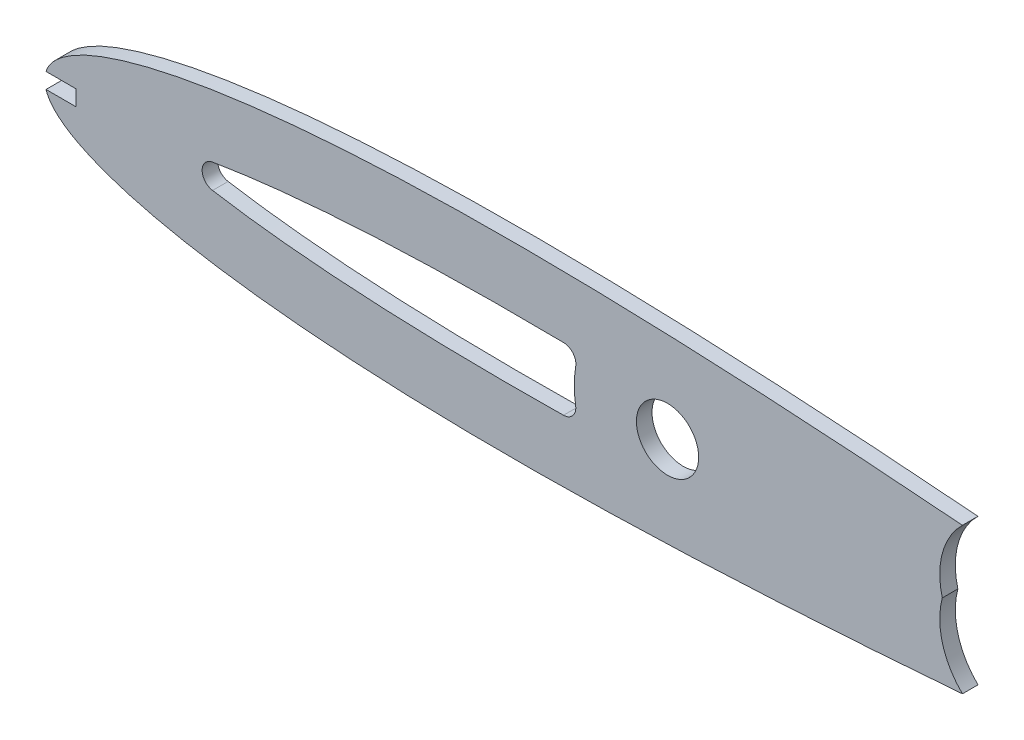
SolidWorks part; units mm, degrees
material "Balsa"
ref_plane "Front Plane" through (0, 0, 0) normal (0, 0, 1) x (1, 0, 0)
ref_plane "Top Plane" through (0, 0, 0) normal (0, 1, 0) x (1, 0, 0)
ref_plane "Right Plane" through (0, 0, 0) normal (1, 0, 0) x (0, 0, -1)
curve "Curve1"
  spline degree 3 poles (318.9616, -0.5388, 0) (318.9616, 0.5388, 0) (317.8871, 0.4072, 0) (316.5257, 0.7904, 0) (314.029, 1.0273, 0) (310.6656, 1.5357, 0) (306.333, 2.103, 0) (301.1081, 2.8022, 0) (295.0047, 3.5926, 0) (288.0667, 4.4725, 0) (280.3349, 5.4267, 0) (271.8575, 6.4421, 0) (262.6867, 7.5062, 0) (252.8789, 8.6045, 0) (242.4947, 9.7236, 0) (231.5982, 10.8496, 0) (220.2564, 11.9679, 0) (208.5394, 13.0629, 0) (196.5193, 14.1202, 0) (184.2704, 15.122, 0) (171.8679, 16.0521, 0) (159.3884, 16.8933, 0) (146.9087, 17.6278, 0) (134.5058, 18.2372, 0) (122.2562, 18.7052, 0) (110.2351, 19.0165, 0) (98.5168, 19.156, 0) (87.1732, 19.1125, 0) (76.2743, 18.8777, 0) (65.8873, 18.4456, 0) (56.076, 17.8151, 0) (46.9007, 16.9881, 0) (38.4176, 15.971, 0) (30.6784, 14.7725, 0) (23.73, 13.4051, 0) (17.6131, 11.8842, 0) (12.3624, 10.2248, 0) (8.0047, 8.4423, 0) (4.5539, 6.5486, 0) (2.0152, 4.5401, 0) (0.3892, 2.3682, 0) (-0.1814, 0, 0) (0.3892, -2.3682, 0) (2.0152, -4.5401, 0) (4.5539, -6.5486, 0) (8.0047, -8.4423, 0) (12.3624, -10.2248, 0) (17.6131, -11.8842, 0) (23.73, -13.4051, 0) (30.6784, -14.7725, 0) (38.4176, -15.971, 0) (46.9007, -16.9881, 0) (56.076, -17.8151, 0) (65.8873, -18.4456, 0) (76.2743, -18.8777, 0) (87.1732, -19.1125, 0) (98.5168, -19.156, 0) (110.2351, -19.0165, 0) (122.2562, -18.7052, 0) (134.5058, -18.2372, 0) (146.9087, -17.6278, 0) (159.3884, -16.8933, 0) (171.8679, -16.0521, 0) (184.2704, -15.122, 0) (196.5193, -14.1202, 0) (208.5394, -13.0629, 0) (220.2564, -11.9679, 0) (231.5982, -10.8496, 0) (242.4947, -9.7236, 0) (252.8789, -8.6045, 0) (262.6867, -7.5062, 0) (271.8575, -6.4421, 0) (280.3349, -5.4267, 0) (288.0667, -4.4725, 0) (295.0047, -3.5926, 0) (301.1081, -2.8022, 0) (306.333, -2.103, 0) (310.6656, -1.5357, 0) (314.029, -1.0273, 0) (316.5257, -0.7904, 0) (317.8871, -0.4072, 0) (318.9616, -0.5388, 0) (318.9616, 0.5388, 0) (317.8871, 0.4072, 0) knots -0.004279 -0.001997 -0.001234 0 0.000762 0.003045 0.006832 0.012101 0.018818 0.026939 0.036415 0.047185 0.05918 0.072328 0.086544 0.101741 0.117823 0.134691 0.15224 0.170361 0.188941 0.207865 0.227016 0.246276 0.265525 0.284645 0.30352 0.322035 0.340078 0.357543 0.374325 0.39033 0.405464 0.419644 0.432793 0.444844 0.455738 0.465429 0.473886 0.481102 0.487102 0.491975 0.495931 0.499383 0.502835 0.50679 0.511664 0.517664 0.524879 0.533337 0.543028 0.553922 0.565972 0.579122 0.593302 0.608436 0.62444 0.641223 0.658687 0.676731 0.695245 0.714121 0.733241 0.75249 0.77175 0.7909 0.809825 0.828404 0.846525 0.864074 0.880942 0.897025 0.912222 0.926438 0.939585 0.951581 0.962351 0.971826 0.979948 0.986664 0.991933 0.995721 0.998003 0.998766 1 1.000762 1.003045 1.006832 periodic
sketch "Sketch2" plane through (0, 0, 0) normal (0, 0, 1) x (1, 0, 0)
  spline S0 degree 3 poles (318.9616, -0.5388) (318.9616, 0.5388) (317.8871, 0.4072) (316.5257, 0.7904) (314.029, 1.0273) (310.6656, 1.5357) (306.333, 2.103) (301.1081, 2.8022) (295.0047, 3.5926) (288.0667, 4.4725) (280.3349, 5.4267) (271.8575, 6.4421) (262.6867, 7.5062) (252.8789, 8.6045) (242.4947, 9.7236) (231.5982, 10.8496) (220.2564, 11.9679) (208.5394, 13.0629) (196.5193, 14.1202) (184.2704, 15.122) (171.8679, 16.0521) (159.3884, 16.8933) (146.9087, 17.6278) (134.5058, 18.2372) (122.2562, 18.7052) (110.2351, 19.0165) (98.5168, 19.156) (87.1732, 19.1125) (76.2743, 18.8777) (65.8873, 18.4456) (56.076, 17.8151) (46.9007, 16.9881) (38.4176, 15.971) (30.6784, 14.7725) (23.73, 13.4051) (17.6131, 11.8842) (12.3624, 10.2248) (8.0047, 8.4423) (4.5539, 6.5486) (2.0152, 4.5401) (0.3892, 2.3682) (-0.1814, 0) (0.3892, -2.3682) (2.0152, -4.5401) (4.5539, -6.5486) (8.0047, -8.4423) (12.3624, -10.2248) (17.6131, -11.8842) (23.73, -13.4051) (30.6784, -14.7725) (38.4176, -15.971) (46.9007, -16.9881) (56.076, -17.8151) (65.8873, -18.4456) (76.2743, -18.8777) (87.1732, -19.1125) (98.5168, -19.156) (110.2351, -19.0165) (122.2562, -18.7052) (134.5058, -18.2372) (146.9087, -17.6278) (159.3884, -16.8933) (171.8679, -16.0521) (184.2704, -15.122) (196.5193, -14.1202) (208.5394, -13.0629) (220.2564, -11.9679) (231.5982, -10.8496) (242.4947, -9.7236) (252.8789, -8.6045) (262.6867, -7.5062) (271.8575, -6.4421) (280.3349, -5.4267) (288.0667, -4.4725) (295.0047, -3.5926) (301.1081, -2.8022) (306.333, -2.103) (310.6656, -1.5357) (314.029, -1.0273) (316.5257, -0.7904) (317.8871, -0.4072) (318.9616, -0.5388) (318.9616, 0.5388) (317.8871, 0.4072) knots -0.004279 -0.001997 -0.001234 0 0.000762 0.003045 0.006832 0.012101 0.018818 0.026939 0.036415 0.047185 0.05918 0.072328 0.086544 0.101741 0.117823 0.134691 0.15224 0.170361 0.188941 0.207865 0.227016 0.246276 0.265525 0.284645 0.30352 0.322035 0.340078 0.357543 0.374325 0.39033 0.405464 0.419644 0.432793 0.444844 0.455738 0.465429 0.473886 0.481102 0.487102 0.491975 0.495931 0.499383 0.502835 0.50679 0.511664 0.517664 0.524879 0.533337 0.543028 0.553922 0.565972 0.579122 0.593302 0.608436 0.62444 0.641223 0.658687 0.676731 0.695245 0.714121 0.733241 0.75249 0.77175 0.7909 0.809825 0.828404 0.846525 0.864074 0.880942 0.897025 0.912222 0.926438 0.939585 0.951581 0.962351 0.971826 0.979948 0.986664 0.991933 0.995721 0.998003 0.998766 1 1.000762 1.003045 1.006832 only from (318.77, 0.4017) to (318.77, 0.4017) construction
  spline S1 degree 3 poles (318.9616, -0.5388) (318.9616, 0.5388) (317.8871, 0.4072) (316.5257, 0.7904) (314.029, 1.0273) (310.6656, 1.5357) (306.333, 2.103) (301.1081, 2.8022) (295.0047, 3.5926) (288.0667, 4.4725) (280.3349, 5.4267) (271.8575, 6.4421) (262.6867, 7.5062) (252.8789, 8.6045) (242.4947, 9.7236) (231.5982, 10.8496) (220.2564, 11.9679) (208.5394, 13.0629) (196.5193, 14.1202) (184.2704, 15.122) (171.8679, 16.0521) (159.3884, 16.8933) (146.9087, 17.6278) (134.5058, 18.2372) (122.2562, 18.7052) (110.2351, 19.0165) (98.5168, 19.156) (87.1732, 19.1125) (76.2743, 18.8777) (65.8873, 18.4456) (56.076, 17.8151) (46.9007, 16.9881) (38.4176, 15.971) (30.6784, 14.7725) (23.73, 13.4051) (17.6131, 11.8842) (12.3624, 10.2248) (8.0047, 8.4423) (4.5539, 6.5486) (2.0152, 4.5401) (0.3892, 2.3682) (-0.1814, 0) (0.3892, -2.3682) (2.0152, -4.5401) (4.5539, -6.5486) (8.0047, -8.4423) (12.3624, -10.2248) (17.6131, -11.8842) (23.73, -13.4051) (30.6784, -14.7725) (38.4176, -15.971) (46.9007, -16.9881) (56.076, -17.8151) (65.8873, -18.4456) (76.2743, -18.8777) (87.1732, -19.1125) (98.5168, -19.156) (110.2351, -19.0165) (122.2562, -18.7052) (134.5058, -18.2372) (146.9087, -17.6278) (159.3884, -16.8933) (171.8679, -16.0521) (184.2704, -15.122) (196.5193, -14.1202) (208.5394, -13.0629) (220.2564, -11.9679) (231.5982, -10.8496) (242.4947, -9.7236) (252.8789, -8.6045) (262.6867, -7.5062) (271.8575, -6.4421) (280.3349, -5.4267) (288.0667, -4.4725) (295.0047, -3.5926) (301.1081, -2.8022) (306.333, -2.103) (310.6656, -1.5357) (314.029, -1.0273) (316.5257, -0.7904) (317.8871, -0.4072) (318.9616, -0.5388) (318.9616, 0.5388) (317.8871, 0.4072) knots -0.004279 -0.001997 -0.001234 0 0.000762 0.003045 0.006832 0.012101 0.018818 0.026939 0.036415 0.047185 0.05918 0.072328 0.086544 0.101741 0.117823 0.134691 0.15224 0.170361 0.188941 0.207865 0.227016 0.246276 0.265525 0.284645 0.30352 0.322035 0.340078 0.357543 0.374325 0.39033 0.405464 0.419644 0.432793 0.444844 0.455738 0.465429 0.473886 0.481102 0.487102 0.491975 0.495931 0.499383 0.502835 0.50679 0.511664 0.517664 0.524879 0.533337 0.543028 0.553922 0.565972 0.579122 0.593302 0.608436 0.62444 0.641223 0.658687 0.676731 0.695245 0.714121 0.733241 0.75249 0.77175 0.7909 0.809825 0.828404 0.846525 0.864074 0.880942 0.897025 0.912222 0.926438 0.939585 0.951581 0.962351 0.971826 0.979948 0.986664 0.991933 0.995721 0.998003 0.998766 1 1.000762 1.003045 1.006832 only from (318.77, 0.4017) to (318.77, 0.4017)
extrude "Boss-Extrude1" add sketch "Sketch2" along normal blind 3.175
sketch "Sketch3" plane through (0, 0, 3.175) normal (0, 0, 1) x (1, 0, 0)
  circle A1 centre (127, 0) radius 6.35
  dimension "D2" = 12.7
  dimension "D4" = 127
  dimension "D6" = 0
extrude "Cut-Extrude1" cut sketch "Sketch3" against normal through all
sketch "Sketch4" plane through (0, 0, 3.175) normal (0, 0, 1) x (1, 0, 0)
  line L5 (6.35, 1.5875) -> (6.35, -1.5875)
  line L6 (6.35, 1.5875) -> (0, 1.5875)
  line L7 (6.35, -1.5875) -> (0, -1.5875)
  line L8 (0, 1.5875) -> (0, -1.5875)
  line L9 (6.35, 1.5875) -> (0, -1.5875) construction
  line L10 (6.35, -1.5875) -> (0, 1.5875) construction
  spline S0 degree 3 poles (318.9616, -0.5388) (318.9616, 0.5388) (317.8871, 0.4072) (316.5257, 0.7904) (314.029, 1.0273) (310.6656, 1.5357) (306.333, 2.103) (301.1081, 2.8022) (295.0047, 3.5926) (288.0667, 4.4725) (280.3349, 5.4267) (271.8575, 6.4421) (262.6867, 7.5062) (252.8789, 8.6045) (242.4947, 9.7236) (231.5982, 10.8496) (220.2564, 11.9679) (208.5394, 13.0629) (196.5193, 14.1202) (184.2704, 15.122) (171.8679, 16.0521) (159.3884, 16.8933) (146.9087, 17.6278) (134.5058, 18.2372) (122.2562, 18.7052) (110.2351, 19.0165) (98.5168, 19.156) (87.1732, 19.1125) (76.2743, 18.8777) (65.8873, 18.4456) (56.076, 17.8151) (46.9007, 16.9881) (38.4176, 15.971) (30.6784, 14.7725) (23.73, 13.4051) (17.6131, 11.8842) (12.3624, 10.2248) (8.0047, 8.4423) (4.5539, 6.5486) (2.0152, 4.5401) (0.3892, 2.3682) (-0.1814, 0) (0.3892, -2.3682) (2.0152, -4.5401) (4.5539, -6.5486) (8.0047, -8.4423) (12.3624, -10.2248) (17.6131, -11.8842) (23.73, -13.4051) (30.6784, -14.7725) (38.4176, -15.971) (46.9007, -16.9881) (56.076, -17.8151) (65.8873, -18.4456) (76.2743, -18.8777) (87.1732, -19.1125) (98.5168, -19.156) (110.2351, -19.0165) (122.2562, -18.7052) (134.5058, -18.2372) (146.9087, -17.6278) (159.3884, -16.8933) (171.8679, -16.0521) (184.2704, -15.122) (196.5193, -14.1202) (208.5394, -13.0629) (220.2564, -11.9679) (231.5982, -10.8496) (242.4947, -9.7236) (252.8789, -8.6045) (262.6867, -7.5062) (271.8575, -6.4421) (280.3349, -5.4267) (288.0667, -4.4725) (295.0047, -3.5926) (301.1081, -2.8022) (306.333, -2.103) (310.6656, -1.5357) (314.029, -1.0273) (316.5257, -0.7904) (317.8871, -0.4072) (318.9616, -0.5388) (318.9616, 0.5388) (317.8871, 0.4072) knots -0.004279 -0.001997 -0.001234 0 0.000762 0.003045 0.006832 0.012101 0.018818 0.026939 0.036415 0.047185 0.05918 0.072328 0.086544 0.101741 0.117823 0.134691 0.15224 0.170361 0.188941 0.207865 0.227016 0.246276 0.265525 0.284645 0.30352 0.322035 0.340078 0.357543 0.374325 0.39033 0.405464 0.419644 0.432793 0.444844 0.455738 0.465429 0.473886 0.481102 0.487102 0.491975 0.495931 0.499383 0.502835 0.50679 0.511664 0.517664 0.524879 0.533337 0.543028 0.553922 0.565972 0.579122 0.593302 0.608436 0.62444 0.641223 0.658687 0.676731 0.695245 0.714121 0.733241 0.75249 0.77175 0.7909 0.809825 0.828404 0.846525 0.864074 0.880942 0.897025 0.912222 0.926438 0.939585 0.951581 0.962351 0.971826 0.979948 0.986664 0.991933 0.995721 0.998003 0.998766 1 1.000762 1.003045 1.006832 only from (318.77, 0.4017) to (318.77, 0.4017) construction
  spline S1 degree 3 poles (44.4469, 16.6766) (42.3575, 16.4398) (37.6765, 15.8562) (30.6784, 14.7725) (23.73, 13.4051) (17.6131, 11.8842) (12.3624, 10.2248) (8.0047, 8.4423) (4.5539, 6.5486) (2.0152, 4.5401) (0.3892, 2.3682) (-0.1814, 0) (0.3892, -2.3682) (2.0152, -4.5401) (4.5539, -6.5486) (8.0047, -8.4423) (12.3624, -10.2248) (17.6131, -11.8842) (23.73, -13.4051) (30.6784, -14.7725) (37.6765, -15.8562) (42.3575, -16.4398) (44.4469, -16.6766) knots 0.4231 0.4231 0.4231 0.4231 0.432793 0.444844 0.455738 0.465429 0.473886 0.481102 0.487102 0.491975 0.495931 0.499383 0.502835 0.50679 0.511664 0.517664 0.524879 0.533337 0.543028 0.553922 0.565972 0.575665 0.575665 0.575665 0.575665
  point P4 (3.175, 0)
  dimension "D2" = 6.35
  dimension "D1" = 3.175
  dimension "D3" = 1.5875
extrude "Cut-Extrude2" cut sketch "Sketch4" against normal through all contours L5 L7 L8 L6
sketch "Sketch5" plane through (0, 0, 3.175) normal (0, 0, 1) x (1, 0, 0)
  line L0 (1.7463, 0) -> (-1.7463, 0) construction
  line L1 (183.0237, 0) -> (228.7437, 0) construction
  line L4 (183.0237, 0) -> (202.931, 5.3341) construction
  line L5 (183.0237, 0) -> (200.3978, -4.6554) construction
  line L6 (188.4413, 14.7763) -> (187.3498, 15.0894)
  line L7 (188.4413, -14.7763) -> (187.2309, -14.9772)
  arc A1 (187.3498, 15.0894) -> (183.0237, 0) centre (197.7444, 3.9444) ccw
  arc A2 (183.0237, 0) -> (187.2309, -14.9772) centre (197.7444, -3.9444) ccw
  spline S0 degree 3 poles (318.9616, -0.5388) (318.9616, 0.5388) (317.8871, 0.4072) (316.5257, 0.7904) (314.029, 1.0273) (310.6656, 1.5357) (306.333, 2.103) (301.1081, 2.8022) (295.0047, 3.5926) (288.0667, 4.4725) (280.3349, 5.4267) (271.8575, 6.4421) (262.6867, 7.5062) (252.8789, 8.6045) (242.4947, 9.7236) (231.5982, 10.8496) (220.2564, 11.9679) (208.5394, 13.0629) (196.5193, 14.1202) (184.2704, 15.122) (171.8679, 16.0521) (159.3884, 16.8933) (146.9087, 17.6278) (134.5058, 18.2372) (122.2562, 18.7052) (110.2351, 19.0165) (98.5168, 19.156) (87.1732, 19.1125) (76.2743, 18.8777) (65.8873, 18.4456) (56.076, 17.8151) (46.9007, 16.9881) (38.4176, 15.971) (30.6784, 14.7725) (23.73, 13.4051) (17.6131, 11.8842) (12.3624, 10.2248) (8.0047, 8.4423) (4.5539, 6.5486) (2.0152, 4.5401) (0.3892, 2.3682) (-0.1814, 0) (0.3892, -2.3682) (2.0152, -4.5401) (4.5539, -6.5486) (8.0047, -8.4423) (12.3624, -10.2248) (17.6131, -11.8842) (23.73, -13.4051) (30.6784, -14.7725) (38.4176, -15.971) (46.9007, -16.9881) (56.076, -17.8151) (65.8873, -18.4456) (76.2743, -18.8777) (87.1732, -19.1125) (98.5168, -19.156) (110.2351, -19.0165) (122.2562, -18.7052) (134.5058, -18.2372) (146.9087, -17.6278) (159.3884, -16.8933) (171.8679, -16.0521) (184.2704, -15.122) (196.5193, -14.1202) (208.5394, -13.0629) (220.2564, -11.9679) (231.5982, -10.8496) (242.4947, -9.7236) (252.8789, -8.6045) (262.6867, -7.5062) (271.8575, -6.4421) (280.3349, -5.4267) (288.0667, -4.4725) (295.0047, -3.5926) (301.1081, -2.8022) (306.333, -2.103) (310.6656, -1.5357) (314.029, -1.0273) (316.5257, -0.7904) (317.8871, -0.4072) (318.9616, -0.5388) (318.9616, 0.5388) (317.8871, 0.4072) knots -0.004279 -0.001997 -0.001234 0 0.000762 0.003045 0.006832 0.012101 0.018818 0.026939 0.036415 0.047185 0.05918 0.072328 0.086544 0.101741 0.117823 0.134691 0.15224 0.170361 0.188941 0.207865 0.227016 0.246276 0.265525 0.284645 0.30352 0.322035 0.340078 0.357543 0.374325 0.39033 0.405464 0.419644 0.432793 0.444844 0.455738 0.465429 0.473886 0.481102 0.487102 0.491975 0.495931 0.499383 0.502835 0.50679 0.511664 0.517664 0.524879 0.533337 0.543028 0.553922 0.565972 0.579122 0.593302 0.608436 0.62444 0.641223 0.658687 0.676731 0.695245 0.714121 0.733241 0.75249 0.77175 0.7909 0.809825 0.828404 0.846525 0.864074 0.880942 0.897025 0.912222 0.926438 0.939585 0.951581 0.962351 0.971826 0.979948 0.986664 0.991933 0.995721 0.998003 0.998766 1 1.000762 1.003045 1.006832 only from (0.2578, -1.5875) to (0.2578, 1.5875) construction
  spline S1 degree 3 poles (188.4413, -14.7763) (191.1589, -14.5572) (197.8927, -13.9994) (208.5394, -13.0629) (220.2564, -11.9679) (231.5982, -10.8496) (242.4947, -9.7236) (252.8789, -8.6045) (262.6867, -7.5062) (271.8575, -6.4421) (280.3349, -5.4267) (288.0667, -4.4725) (295.0047, -3.5926) (301.1081, -2.8022) (306.333, -2.103) (310.6656, -1.5357) (314.029, -1.0273) (316.5257, -0.7904) (317.8871, -0.4072) (318.9616, -0.5388) (318.9616, 0.5388) (317.8871, 0.4072) (316.5257, 0.7904) (314.029, 1.0273) (310.6656, 1.5357) (306.333, 2.103) (301.1081, 2.8022) (295.0047, 3.5926) (288.0667, 4.4725) (280.3349, 5.4267) (271.8575, 6.4421) (262.6867, 7.5062) (252.8789, 8.6045) (242.4947, 9.7236) (231.5982, 10.8496) (220.2564, 11.9679) (208.5394, 13.0629) (197.8927, 13.9994) (191.1589, 14.5572) (188.4413, 14.7763) knots 0.797256 0.797256 0.797256 0.797256 0.809825 0.828404 0.846525 0.864074 0.880942 0.897025 0.912222 0.926438 0.939585 0.951581 0.962351 0.971826 0.979948 0.986664 0.991933 0.995721 0.998003 0.998766 1 1.000762 1.003045 1.006832 1.012101 1.018818 1.026939 1.036415 1.047185 1.05918 1.072328 1.086544 1.101741 1.117823 1.134691 1.15224 1.170361 1.188941 1.20151 1.20151 1.20151 1.20151
  point P0 (318.9137, 0)
  dimension "D5" = 30.48
  dimension "D6" = 30.48
  dimension "D1" = 135.89
  dimension "D3" = 15
  dimension "D4" = 15
extrude "Cut-Extrude3" cut sketch "Sketch5" against normal through all
sketch "Sketch7" plane through (0, 0, 3.175) normal (0, 0, 1) x (1, 0, 0)
  arc A2 (109.0688, 6.4323) -> (109.025, -6.3089) centre (127, 0) ccw
  spline S1 degree 3 poles (109.0688, 6.4323) (107.3237, 6.4634) (103.8498, 6.5143) (94.8433, 6.5858) (80.703, 6.4846) (64.9446, 5.8628) (51.4086, 4.8085) (43.0528, 3.887) (36.4764, 2.9518) (31.6149, 2.1356) (27.6591, 1.3481) (24.6595, 0.6621) (23.2116, 0.2998) (22.4642, 0.1036) (22.3668, 0.0778) (22.3075, 0.0621) knots 0.323322 0.323322 0.323322 0.323322 0.331491 0.339592 0.365545 0.397949 0.41415 0.430352 0.438453 0.446553 0.454654 0.458705 0.462223 0.462436 0.462755 0.462755 0.462755 0.462755
  spline S66 degree 3 poles (22.3075, 0.0621) (22.3668, 0.0464) (22.4642, 0.0206) (23.2116, -0.1756) (24.6595, -0.5379) (27.6591, -1.2239) (31.6149, -2.0114) (36.4764, -2.8276) (43.0528, -3.7628) (51.4086, -4.6843) (64.9446, -5.7386) (80.703, -6.3604) (94.8433, -6.4616) (103.8352, -6.3902) (107.2946, -6.3396) (109.025, -6.3089) knots 0.536011 0.536011 0.536011 0.536011 0.53633 0.536543 0.540061 0.544111 0.552212 0.560313 0.568414 0.584615 0.600817 0.63322 0.659174 0.667275 0.675376 0.675376 0.675376 0.675376
extrude "Cut-Extrude4" cut sketch "Sketch7" against normal through all
fillet "Fillet1" radius 2.54 3 edges at (22.3075, 0.0621, 1.5875)
fillet "Fillet2" radius 2.54 2 edges at (109.025, -6.3089, 1.5875) (109.0688, 6.4323, 1.5875)
